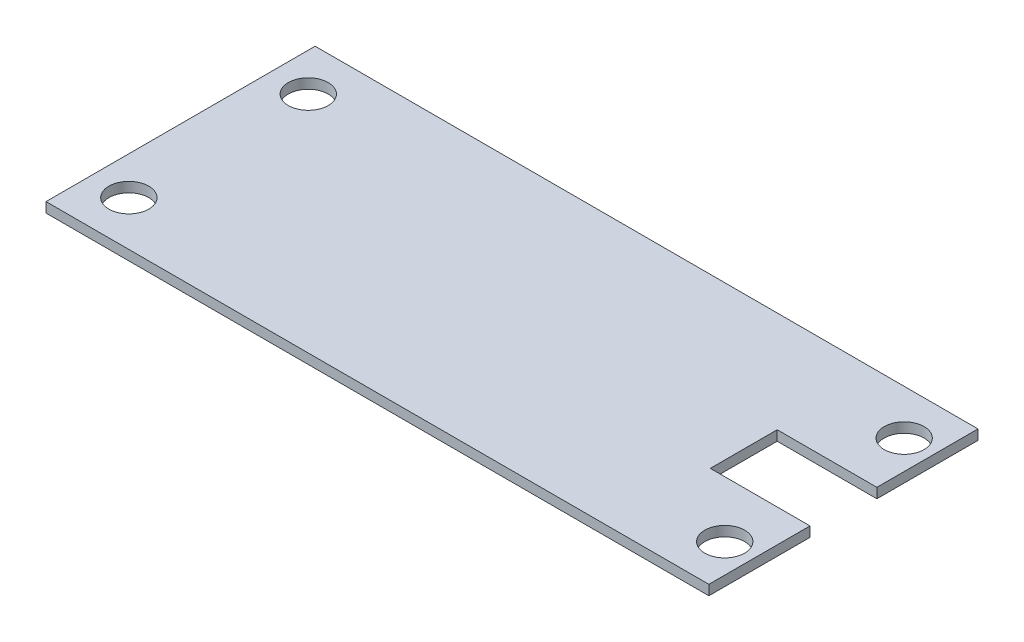
SolidWorks part; units mm, degrees
ref_plane "Front Plane" through (0, 0, 0) normal (0, 0, 1) x (1, 0, 0)
ref_plane "Top Plane" through (0, 0, 0) normal (0, 1, 0) x (1, 0, 0)
ref_plane "Right Plane" through (0, 0, 0) normal (1, 0, 0) x (0, 0, -1)
sketch "Sketch1" plane through (0, 0, 0) normal (0, 1, 0) x (1, 0, 0)
  line L1 (0, 0) -> (66.5, 0)
  line L2 (0, 0) -> (0, 27)
  line L3 (0, 27) -> (66.5, 27)
  line L4 (66.5, 0) -> (66.5, 27)
  dimension "D1" = 66.5
  dimension "D2" = 27
extrude "Boss-Extrude1" add sketch "Sketch1" along normal blind 1
sketch "Sketch2" plane through (66.5, 0, 0) normal (1, 0, 0) x (0, 0, -1)
  line L0 (0, 0) -> (27, 0) construction
  line L2 (10.1461, 0) -> (10.1461, 2.5837)
  line L3 (10.1461, 2.5837) -> (16.8539, 2.5837)
  line L4 (16.8539, 0) -> (16.8539, 2.5837)
  line L6 (0, 0) -> (10.1461, 0)
  line L7 (16.8539, 0) -> (27, 0)
extrude "Cut-Extrude1" cut sketch "Sketch2" against normal blind 10 and the other way through all
sketch "Sketch3" plane through (0, 1, 0) normal (0, 1, 0) x (1, 0, 0)
  line L0 (66.5, 27) -> (0, 27) construction
  circle A0 centre (63.5912, 4.5) radius 2
  circle A1 centre (63.5912, 22.5) radius 2
  circle A2 centre (3.8128, 22.5) radius 2
  circle A3 centre (3.8128, 4.5) radius 2
  dimension "D1" = 4
  dimension "D2" = 18
  dimension "D3" = 4.5
extrude "Cut-Extrude2" cut sketch "Sketch3" against normal through all
